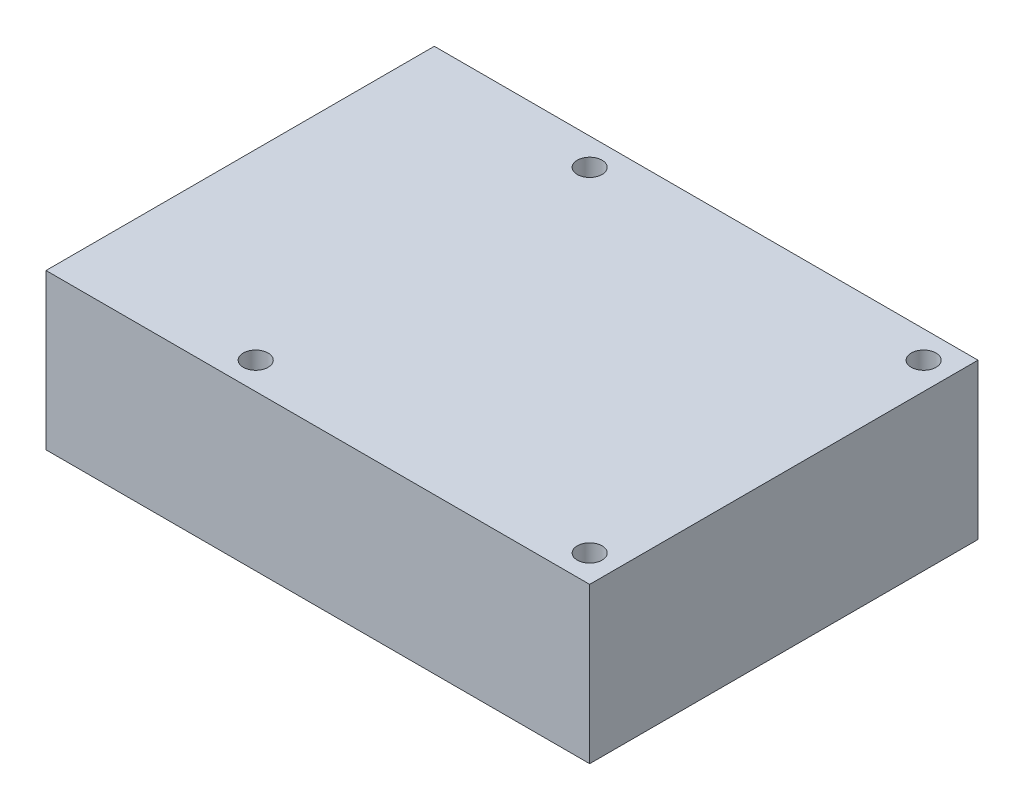
SolidWorks part; units mm, degrees
ref_plane "Front Plane" through (0, 0, 0) normal (0, 0, 1) x (1, 0, 0)
ref_plane "Top Plane" through (0, 0, 0) normal (0, 1, 0) x (1, 0, 0)
ref_plane "Right Plane" through (0, 0, 0) normal (1, 0, 0) x (0, 0, -1)
sketch "Sketch1" plane through (0, 0, 0) normal (0, 1, 0) x (1, 0, 0)
  line L1 (-25, -25) -> (25, -25)
  line L2 (-25, -25) -> (-25, 25)
  line L3 (-25, 25) -> (25, 25)
  line L4 (25, -25) -> (25, 25)
  line L5 (-25, -25) -> (25, 25) construction
  line L6 (-25, 25) -> (25, -25) construction
  circle A2 centre (21.5, 21.5) radius 1.6
  circle A3 centre (21.5, -21.5) radius 1.6
  circle A4 centre (-21.5, -21.5) radius 1.6
  circle A5 centre (-21.5, 21.5) radius 1.6
  point P0 (0, 0)
  point P6 (0, 0)
  point P17 (0, 0)
  dimension "D1" = 50
  dimension "D2" = 4
  dimension "D3" = 43
extrude "Boss-Extrude1" add sketch "Sketch1" along normal blind 20
sketch "Sketch2" plane through (0, 20, 0) normal (0, 1, 0) x (1, 0, 0)
  line L0 (24.6754, 21.5) -> (23.0877, 24.25)
  line L1 (-21.5, 24.6754) -> (-24.25, 23.0877)
  line L2 (-24.25, 23.0877) -> (-24.25, 19.9123)
  line L3 (-24.25, 19.9123) -> (-21.5, 18.3246)
  line L4 (-21.5, 18.3246) -> (-18.75, 19.9123)
  line L5 (-18.75, 19.9123) -> (-18.75, 23.0877)
  line L6 (-18.75, 23.0877) -> (-21.5, 24.6754)
  line L7 (23.0877, 24.25) -> (19.9123, 24.25)
  line L8 (19.9123, 24.25) -> (18.3246, 21.5)
  line L9 (18.3246, 21.5) -> (19.9123, 18.75)
  line L10 (19.9123, 18.75) -> (23.0877, 18.75)
  line L11 (23.0877, 18.75) -> (24.6754, 21.5)
  line L12 (21.5, -24.6754) -> (24.25, -23.0877)
  line L13 (24.25, -23.0877) -> (24.25, -19.9123)
  line L14 (24.25, -19.9123) -> (21.5, -18.3246)
  line L15 (21.5, -18.3246) -> (18.75, -19.9123)
  line L16 (18.75, -19.9123) -> (18.75, -23.0877)
  line L17 (18.75, -23.0877) -> (21.5, -24.6754)
  line L18 (-24.6754, -21.5) -> (-23.0877, -24.25)
  line L19 (-23.0877, -24.25) -> (-19.9123, -24.25)
  line L20 (-19.9123, -24.25) -> (-18.3246, -21.5)
  line L21 (-18.3246, -21.5) -> (-19.9123, -18.75)
  line L22 (-19.9123, -18.75) -> (-23.0877, -18.75)
  line L23 (-23.0877, -18.75) -> (-24.6754, -21.5)
  circle A0 centre (-21.5, 21.5) radius 2.75 construction
  point P30 (0, 0)
  dimension "D1" = 5.5
  dimension "D2" = 4
extrude "Cut-Extrude1" cut sketch "Sketch2" against normal blind 2.3 from offset 5 offset against normal yes
sketch "Sketch3" plane through (-25, 0, 0) normal (-1, 0, 0) x (0, 0, 1)
  line L4 (-25, 0) -> (25, 0)
  line L5 (25, 0) -> (25, 20)
  line L6 (25, 20) -> (-25, 20)
  line L7 (-25, 20) -> (-25, 0)
  line L8 (-25, 0) -> (25, 0)
  line L9 (25, 0) -> (25, 20)
  line L10 (25, 20) -> (-25, 20)
  line L11 (-25, 20) -> (-25, 0)
  dimension "D1" = 0
extrude "Boss-Extrude2" add sketch "Sketch3" along normal blind 20
